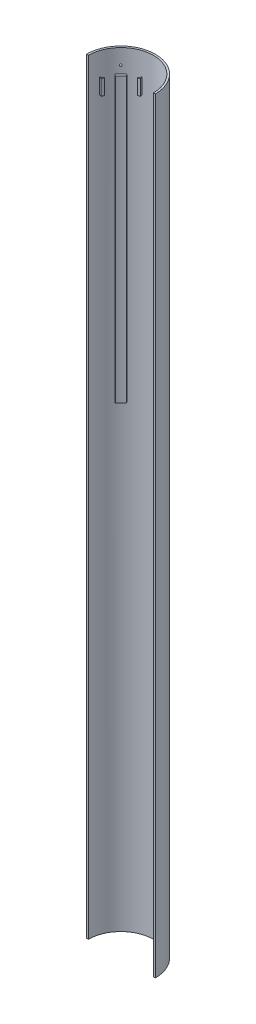
SolidWorks part; units mm, degrees
ref_plane "前视基准面" through (0, 0, 0) normal (0, 0, 1) x (1, 0, 0)
ref_plane "上视基准面" through (0, 0, 0) normal (0, 1, 0) x (1, 0, 0)
ref_plane "右视基准面" through (0, 0, 0) normal (1, 0, 0) x (0, 0, -1)
other "Configuration Table"
sketch "草图1" plane through (0, 0, 0) normal (0, 1, 0) x (1, 0, 0)
  line L1 (-45, 0) -> (-42.5, 0)
  line L2 (42.5, 0) -> (45, 0)
  arc A0 (45, 0) -> (-45, 0) centre (0, 0) ccw
  arc A1 (42.5, 0) -> (-42.5, 0) centre (0, 0) ccw
  dimension "D1" = 90
  dimension "D2" = 85
extrude "凸台-拉伸1" add sketch "草图1" along normal blind 1000
sketch "草图3" plane through (0, 1000, 0) normal (0, 1, 0) x (1, 0, 0)
  line L0 (-40, 0) -> (40, 0) construction
  line L1 (0, 0) -> (0, 45) construction
  line L2 (-31.3375, 24.0461) -> (-33.7175, 25.8724)
  line L3 (-24.0461, 31.3375) -> (-25.8724, 33.7175)
  line L4 (24.0461, 31.3375) -> (25.8724, 33.7175)
  line L5 (31.3375, 24.0461) -> (33.7175, 25.8724)
  arc A0 (33.7175, 25.8724) -> (25.8724, 33.7175) centre (0, 0) ccw
  arc A1 (31.3375, 24.0461) -> (24.0461, 31.3375) centre (0, 0) ccw
  arc A2 (-24.0461, 31.3375) -> (-31.3375, 24.0461) centre (0, 0) ccw
  arc A3 (-25.8724, 33.7175) -> (-33.7175, 25.8724) centre (0, 0) ccw
  arc A4 (45, 0) -> (-45, 0) centre (0, 0) ccw construction
  dimension "D1" = 79
  dimension "D6" = 42.5
  dimension "D2" = 37.5
  dimension "D3" = 37.5
  dimension "D4" = 37.5
  dimension "D5" = 37.5
extrude "凸台-拉伸3" add sketch "草图3" against normal blind 370 from offset 30 offset against normal yes
sketch "草图4" plane through (0, 1000, 0) normal (0, 1, 0) x (1, 0, 0)
  line L0 (-42.5, 0) -> (40, 0) construction
  line L1 (0, 0) -> (0, 42.5) construction
  line L2 (-37.6718, 11.8779) -> (-40.533, 12.78)
  line L3 (-36.5458, 14.9885) -> (-39.3214, 16.1269)
  line L4 (36.5458, 14.9885) -> (39.3214, 16.1269)
  line L5 (37.6718, 11.8779) -> (40.533, 12.78)
  line L6 (11.8779, 37.6718) -> (12.78, 40.533)
  line L7 (14.9885, 36.5458) -> (16.1269, 39.3214)
  line L8 (-14.9885, 36.5458) -> (-16.1269, 39.3214)
  line L9 (-11.8779, 37.6718) -> (-12.78, 40.533)
  arc A0 (40.533, 12.78) -> (39.3214, 16.1269) centre (0, 0) ccw
  arc A1 (37.6718, 11.8779) -> (36.5458, 14.9885) centre (0, 0) ccw
  arc A2 (-36.5458, 14.9885) -> (-37.6718, 11.8779) centre (0, 0) ccw
  arc A3 (-39.3214, 16.1269) -> (-40.533, 12.78) centre (0, 0) ccw
  arc A4 (-11.8779, 37.6718) -> (-14.9885, 36.5458) centre (0, 0) ccw
  arc A5 (-12.78, 40.533) -> (-16.1269, 39.3214) centre (0, 0) ccw
  arc A6 (14.9885, 36.5458) -> (11.8779, 37.6718) centre (0, 0) ccw
  arc A7 (16.1269, 39.3214) -> (12.78, 40.533) centre (0, 0) ccw
  arc A8 (42.5, 0) -> (-42.5, 0) centre (0, 0) ccw construction
  dimension "D9" = 42.5
  dimension "D10" = 39.5
  dimension "D1" = 22.3
  dimension "D2" = 17.5
  dimension "D3" = 22.3
  dimension "D4" = 17.5
  dimension "D5" = 17.5
  dimension "D6" = 22.3
  dimension "D7" = 22.3
  dimension "D8" = 17.5
extrude "凸台-拉伸4" add sketch "草图4" against normal blind 20 from offset 30 offset against normal yes
sketch "草图5" plane through (0, 970, 0) normal (0, 1, 0) x (1, 0, 0)
  line L0 (-38.2935, 13.1855) -> (-40.1845, 13.8366)
  line L1 (-37.4441, 15.4334) -> (-39.3214, 16.1269)
  line L2 (-15.4334, 37.4441) -> (-16.1269, 39.3214)
  line L3 (-13.1855, 38.2935) -> (-13.8366, 40.1845)
  line L4 (13.1855, 38.2935) -> (13.8366, 40.1845)
  line L5 (15.4334, 37.4441) -> (16.1269, 39.3214)
  line L6 (37.4441, 15.4334) -> (39.3214, 16.1269)
  line L7 (38.2935, 13.1855) -> (40.1845, 13.8366)
  line L8 (-42.5, 0) -> (42.5, 0) construction
  line L9 (0, 0) -> (0, 42.5) construction
  arc A0 (40.1845, 13.8366) -> (39.3214, 16.1269) centre (0, 0) ccw
  arc A1 (38.2935, 13.1855) -> (37.4441, 15.4334) centre (0, 0) ccw
  arc A2 (-39.3214, 16.1269) -> (-40.1845, 13.8366) centre (0, 0) ccw
  arc A3 (-37.4441, 15.4334) -> (-38.2935, 13.1855) centre (0, 0) ccw
  arc A4 (-13.8366, 40.1845) -> (-16.1269, 39.3214) centre (0, 0) ccw
  arc A5 (-13.1855, 38.2935) -> (-15.4334, 37.4441) centre (0, 0) ccw
  arc A6 (16.1269, 39.3214) -> (13.8366, 40.1845) centre (0, 0) ccw
  arc A7 (15.4334, 37.4441) -> (13.1855, 38.2935) centre (0, 0) ccw
  arc A8 (42.5, 0) -> (-42.5, 0) centre (0, 0) ccw construction
  dimension "D1" = 81
  dimension "D2" = 19
  dimension "D3" = 19
  dimension "D4" = 19
  dimension "D5" = 19
extrude "切除-拉伸1" cut sketch "草图5" against normal blind 20
ref_plane "基准面1" through (-31.8198, 0, -31.8198) normal (-0.7071, 0, -0.7071) x (0, -1, 0)
sketch "草图8" plane through (-31.8198, 0, -31.8198) normal (-0.7071, 0, -0.7071) x (0, -1, 0)
  line L0 (-970, 0) -> (-980, 0) construction
  line L1 (-970, -5.696) -> (-970, 5.696) construction
  line L2 (-1000, 31.8198) -> (-1000, -45) construction
  circle A0 centre (-980, 0) radius 2.7
  dimension "D1" = 5.4
  dimension "D2" = 20
extrude "切除-拉伸4" cut sketch "草图8" against normal blind 2
sketch "草图9" plane through (-31.8198, 0, -31.8198) normal (-0.7071, 0, -0.7071) x (0, -1, 0)
  line L0 (-970, 0) -> (-980, 0) construction
  line L1 (-970, -5.696) -> (-970, 5.696) construction
  line L3 (-1000, 31.8198) -> (-1000, -45) construction
  circle A0 centre (-980, 0) radius 1.25
  dimension "D1" = 2.5
  dimension "D2" = 20
extrude "切除-拉伸5" cut sketch "草图9" against normal blind 6
ref_plane "基准面2" through (31.8198, 0, -31.8198) normal (0.7071, 0, -0.7071) x (0, -1, 0)
sketch "草图10" plane through (31.8198, 0, -31.8198) normal (0.7071, 0, -0.7071) x (0, -1, 0)
  line L0 (-970, 0) -> (-980, 0) construction
  line L1 (-970, -5.696) -> (-970, 5.696) construction
  line L2 (-1000, 45) -> (-1000, -31.8198) construction
  circle A0 centre (-980, 0) radius 2.7
  dimension "D1" = 5.4
  dimension "D2" = 20
extrude "切除-拉伸6" cut sketch "草图10" against normal blind 2
sketch "草图11" plane through (31.8198, 0, -31.8198) normal (0.7071, 0, -0.7071) x (0, -1, 0)
  line L0 (-970, 0) -> (-980, 0) construction
  line L1 (-970, -5.696) -> (-970, 5.696) construction
  line L2 (-1000, 45) -> (-1000, -31.8198) construction
  circle A0 centre (-980, 0) radius 1.25
  dimension "D1" = 2.5
  dimension "D2" = 20
extrude "切除-拉伸7" cut sketch "草图11" against normal blind 6
